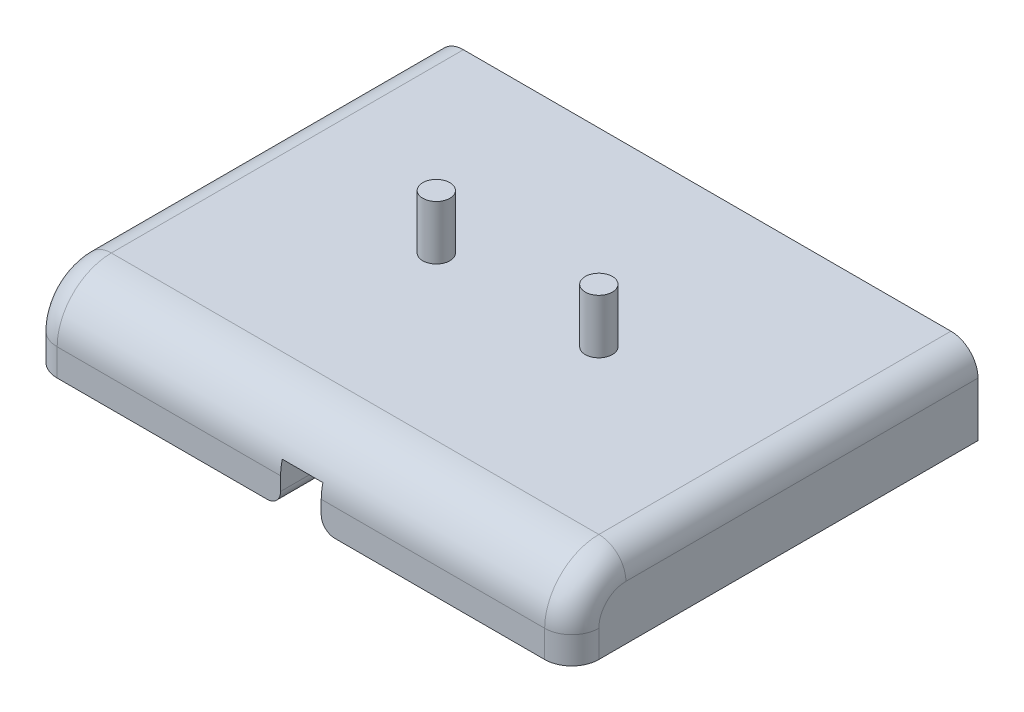
SolidWorks part; units mm, degrees
material "Custom Plastic"
ref_plane "Front Plane" through (0, 0, 0) normal (0, 0, 1) x (1, 0, 0)
ref_plane "Top Plane" through (0, 0, 0) normal (0, 1, 0) x (1, 0, 0)
ref_plane "Right Plane" through (0, 0, 0) normal (1, 0, 0) x (0, 0, -1)
sketch "Sketch1" plane through (0, 0, 0) normal (0, 1, 0) x (1, 0, 0)
  line L0 (0, -55) -> (0, 55) construction
  line L1 (-100, 75) -> (100, 75)
  line L2 (-100, 75) -> (-100, -75)
  line L3 (-100, -75) -> (100, -75)
  line L4 (100, 75) -> (100, -75)
  point P4 (0, 75)
  point P9 (-100, 0)
  dimension "D1" = 150
  dimension "D2" = 200
extrude "Boss-Extrude1" add sketch "Sketch1" along normal blind 30 contours L3 L4 L1 L2
fillet "Fillet1" radius 20 1 edges at (0, 30, 75)
fillet "Fillet2" radius 10 6 edges at (100, 30, -10) (100, 24.1421, 69.1421) (100, 5, 75) (-100, 5, 75) (-100, 24.1421, 69.1421) (-100, 30, -10)
sketch "Sketch2" plane through (0, 0, 75) normal (0, 0, 1) x (1, 0, 0)
  line L0 (-90, 0) -> (90, 0) construction
  line L1 (-7.5, 0) -> (7.5, 0)
  line L2 (-7.5, 0) -> (-7.5, 15)
  line L3 (-7.5, 15) -> (7.5, 15)
  line L4 (7.5, 0) -> (7.5, 15)
  line L5 (0, -55) -> (0, 55) construction
  point P6 (0, 15)
  dimension "D1" = 15
  dimension "D2" = 15
extrude "Cut-Extrude1" cut sketch "Sketch2" against normal through all
fillet "Fillet4" radius 5 2 edges at (7.5, 0, 0) (-7.5, 0, 0)
sketch "Sketch3" plane through (0, 30, 0) normal (0, 1, 0) x (1, 0, 0)
  line L0 (0, -16.5) -> (0, 16.5) construction
  line L1 (-90, 75) -> (90, 75) construction
  circle A0 centre (30, 5) radius 5
  dimension "D2" = 10
  dimension "D1" = 30
  dimension "D3" = 70
extrude "Boss-Extrude2" add sketch "Sketch3" along normal blind 20 contours A0
mirror "Mirror1" about plane through (0, 0, 0) normal (1, 0, 0) of "Boss-Extrude2"
